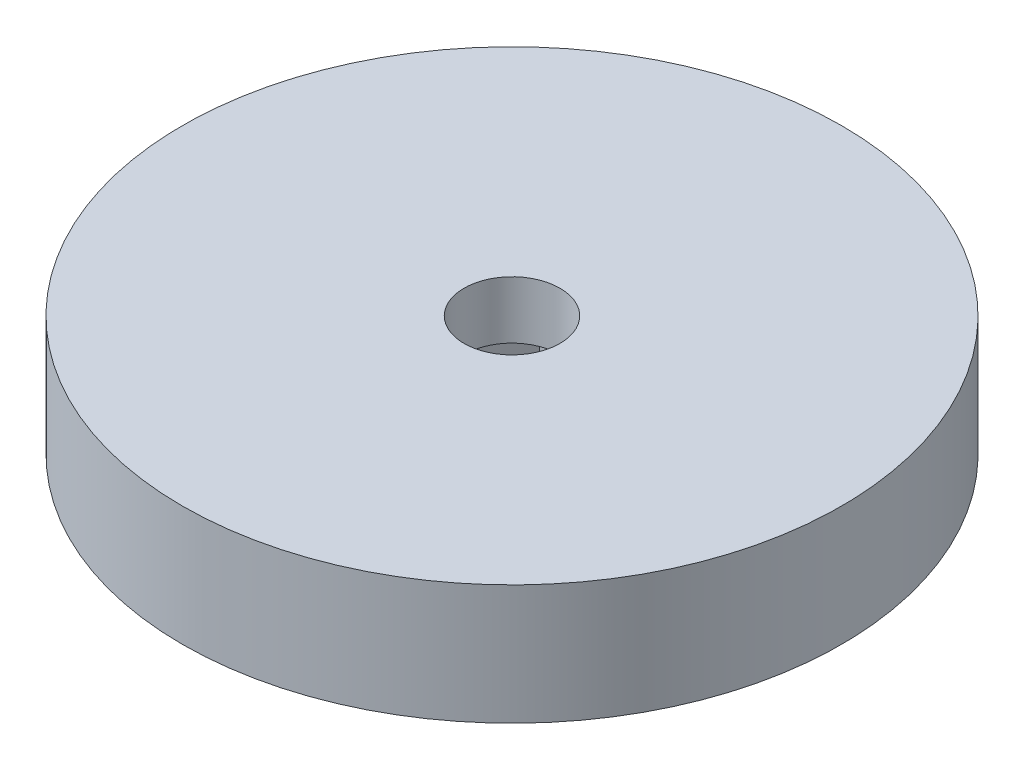
SolidWorks part; units mm, degrees
ref_plane "Front Plane" through (0, 0, 0) normal (0, 0, 1) x (1, 0, 0)
ref_plane "Top Plane" through (0, 0, 0) normal (0, 1, 0) x (1, 0, 0)
ref_plane "Right Plane" through (0, 0, 0) normal (1, 0, 0) x (0, 0, -1)
sketch "Sketch1" plane through (0, 0, 0) normal (0, 1, 0) x (1, 0, 0)
  circle A0 centre (0, 0) radius 24.384 construction
  circle A1 centre (0, 0) radius 34.384
  dimension "D1" = 48.768
  dimension "D2" = 10
extrude "Boss-Extrude1" add sketch "Sketch1" along normal blind 12.5
hole_wizard "Ø10.0mm Dowel Hole1" positions "Sketch3" profile "Sketch2" hole size "Ø10.0" standard "ANSI Metric" end condition through all
sketch "Sketch3" plane through (0, 0, 0) normal (0, -1, 0) x (-1, 0, 0)
  point P0 (0, 0)
sketch "Sketch2" plane through (0, 0, 0) normal (1, 0, 0) x (0, 0, -1)
  line L0 (0, 0) -> (0, 12.5)
  line L1 (0, 12.5) -> (5, 12.5)
  line L2 (5, 12.5) -> (5, 0)
  line L5 (5, 0) -> (0, 0)
  line L11 (0, -6.35) -> (0, 107.95) construction
  dimension "Thru Hole Dia." = 10
  dimension "Thru Hole Depth" = 12.5
sketch "Sketch4" plane through (0, 0, 0) normal (0, -1, 0) x (-1, 0, 0)
  line L1 (-3.8971, -6.75) -> (3.8971, -6.75)
  line L2 (3.8971, -6.75) -> (7.7942, 0)
  line L3 (7.7942, 0) -> (3.8971, 6.75)
  line L4 (3.8971, 6.75) -> (-3.8971, 6.75)
  line L5 (-3.8971, 6.75) -> (-7.7942, 0)
  line L6 (-7.7942, 0) -> (-3.8971, -6.75)
  circle A0 centre (0, 0) radius 6.75 construction
  dimension "D1" = 13.5
extrude "Cut-Extrude1" cut sketch "Sketch4" against normal blind 6.5
